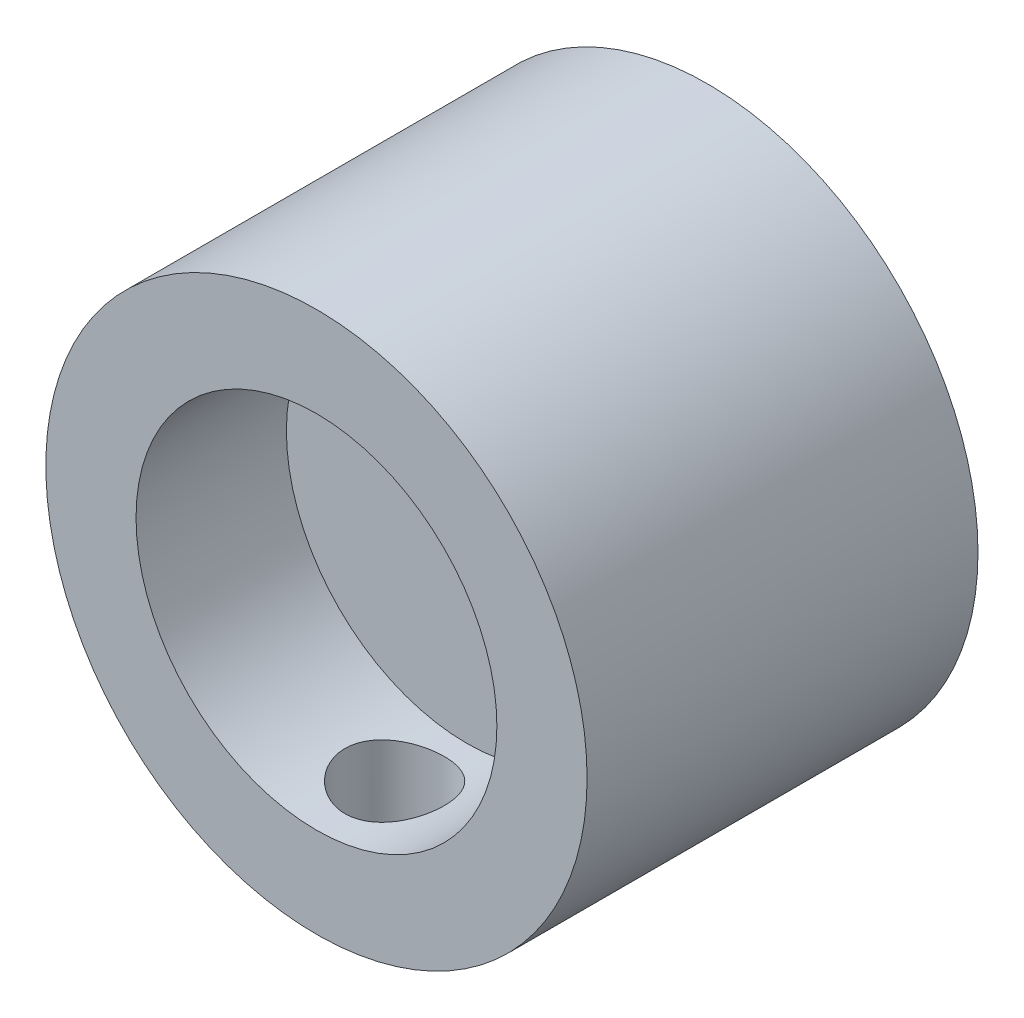
SolidWorks part; units mm, degrees
ref_plane "Front Plane" through (0, 0, 0) normal (0, 0, 1) x (1, 0, 0)
ref_plane "Top Plane" through (0, 0, 0) normal (0, 1, 0) x (1, 0, 0)
ref_plane "Right Plane" through (0, 0, 0) normal (1, 0, 0) x (0, 0, -1)
sketch "Sketch3" plane through (0, 0, 0) normal (0, 0, 1) x (1, 0, 0)
  circle A0 centre (0, 0) radius 4.5
  dimension "D1" = 9
extrude "Boss-Extrude3" add sketch "Sketch3" along normal blind 6.5
sketch "Sketch4" plane through (0, 0, 6.5) normal (0, 0, 1) x (1, 0, 0)
  circle A0 centre (0, 0) radius 3
  dimension "D1" = 6
extrude "Cut-Extrude1" cut sketch "Sketch4" against normal blind 2.5
sketch "Sketch5" plane through (0, 0, 0) normal (0, 0, -1) x (-1, 0, 0)
  circle A0 centre (0, 0) radius 2
  dimension "D1" = 4
extrude "Cut-Extrude2" cut sketch "Sketch5" against normal blind 1.95
sketch "Sketch7" plane through (0, 0, 0) normal (0, 1, 0) x (1, 0, 0)
  line L0 (0, 0) -> (0, -6.5) construction
  line L1 (4.5, 0) -> (-4.5, 0) construction
  line L2 (-4.5, -6.5) -> (4.5, -6.5) construction
  circle A0 centre (0, -5.2) radius 0.825
  dimension "D1" = 1.65
  dimension "D2" = 1.3
extrude "Cut-Extrude3" cut sketch "Sketch7" against normal up to next
